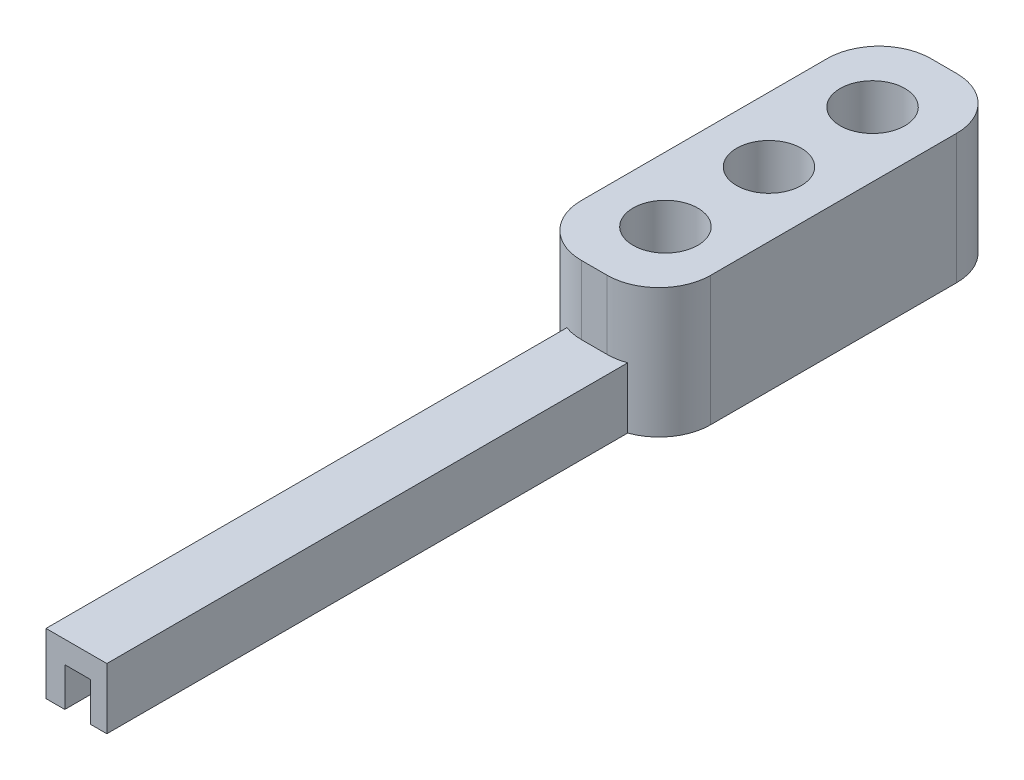
SolidWorks part; units mm, degrees
ref_plane "Front Plane" through (0, 0, 0) normal (0, 0, 1) x (1, 0, 0)
ref_plane "Top Plane" through (0, 0, 0) normal (0, 1, 0) x (1, 0, 0)
ref_plane "Right Plane" through (0, 0, 0) normal (1, 0, 0) x (0, 0, -1)
sketch "Sketch1" plane through (0, 0, 0) normal (0, 1, 0) x (1, 0, 0)
  line L1 (-4.8536, 23.9676) -> (5.1464, 23.9676)
  line L2 (-4.8536, 23.9676) -> (-4.8536, -3.0324)
  line L3 (-4.8536, -3.0324) -> (5.1464, -3.0324)
  line L4 (5.1464, 23.9676) -> (5.1464, -3.0324)
  dimension "D1" = 10
  dimension "D2" = 27
extrude "Boss-Extrude1" add sketch "Sketch1" along normal blind 10
sketch "Sketch2" plane through (0, 10, 0) normal (0, 1, 0) x (1, 0, 0)
  line L0 (5.1464, 23.9676) -> (-4.8536, 23.9676) construction
  line L1 (5.1464, -3.0324) -> (5.1464, 23.9676) construction
  circle A0 centre (0.1464, 18.4676) radius 2.5
  circle A1 centre (0.1464, 10.4676) radius 2.5
  circle A2 centre (0.1464, 2.4676) radius 2.5
  dimension "D1" = 5.5
  dimension "D2" = 5
  dimension "D3" = 5
  dimension "D4" = 3
extrude "Cut-Extrude1" cut sketch "Sketch2" against normal blind 10
sketch "Sketch3" plane through (0, 0, 3.0324) normal (0, 0, 1) x (1, 0, 0)
  line L0 (-4.8536, 0) -> (5.1464, 0) construction
  line L1 (-2.2036, 0) -> (2.4964, 0)
  line L2 (-2.2036, 0) -> (-2.2036, 4.7)
  line L3 (-2.2036, 4.7) -> (2.4964, 4.7)
  line L4 (2.4964, 0) -> (2.4964, 4.7)
  line L5 (5.1464, 10) -> (5.1464, 0) construction
  line L6 (-4.8536, 10) -> (-4.8536, 0) construction
  dimension "D1" = 2.65
  dimension "D2" = 2.65
  dimension "D3" = 4.7
extrude "Boss-Extrude2" add sketch "Sketch3" along normal blind 40
sketch "Sketch4" plane through (0, 0, 0) normal (0, -1, 0) x (-1, 0, 0)
  line L0 (2.2036, -43.0324) -> (-2.4964, -43.0324) construction
  line L1 (-1.2464, -43.0324) -> (0.7536, -43.0324)
  line L2 (-1.2464, -43.0324) -> (-1.2464, 18.9676)
  line L4 (0.7536, -43.0324) -> (0.7536, 18.9676)
  line L6 (-2.4964, -43.0324) -> (-2.4964, -3.0324) construction
  line L8 (-1.2464, 18.9676) -> (0.7536, 18.9676)
  line L9 (-5.1464, 23.9676) -> (4.8536, 23.9676) construction
  dimension "D1" = 1.25
  dimension "D2" = 2
  dimension "D3" = 5
extrude "Cut-Extrude3" cut sketch "Sketch4" against normal blind 3
fillet "Fillet1" radius 4 4 edges at (5.1464, 5, 3.0324) (-4.8536, 5, 3.0324) (-4.8536, 5, -23.9676) (5.1464, 5, -23.9676)
sketch "Sketch5" plane through (0, 0, 0) normal (0, -1, 0) x (-1, 0, 0)
  circle A0 centre (-0.1464, 18.4676) radius 3
  circle A1 centre (-0.1464, 10.4676) radius 3
  circle A2 centre (-0.1464, 2.4676) radius 3
  dimension "D1" = 6
  dimension "D2" = 3
extrude "Cut-Extrude4" cut sketch "Sketch5" against normal blind 3
sketch "Sketch6" plane through (0, 0, 0) normal (0, -1, 0) x (-1, 0, 0)
  line L2 (-0.1464, 18.4676) -> (-0.1464, 18.9676)
  line L3 (-0.1464, 18.9676) -> (4.8536, 18.9676)
  line L4 (4.8536, 18.4676) -> (4.8536, 18.9676)
  line L6 (-0.1464, 10.4676) -> (-0.1464, 10.9676)
  line L7 (-0.1464, 10.9676) -> (4.8536, 10.9676)
  line L8 (4.8536, 10.4676) -> (4.8536, 10.9676)
  line L10 (-0.1464, 2.4676) -> (-0.1464, 2.9676)
  line L11 (-0.1464, 2.9676) -> (4.8536, 2.9676)
  line L12 (4.8536, 2.4676) -> (4.8536, 2.9676)
  line L14 (-0.1464, 18.4676) -> (-0.1464, 17.9676)
  line L15 (-0.1464, 17.9676) -> (4.8536, 17.9676)
  line L16 (4.8536, 18.4676) -> (4.8536, 17.9676)
  line L18 (-0.1464, 10.4676) -> (-0.1464, 9.9676)
  line L19 (-0.1464, 9.9676) -> (4.8536, 9.9676)
  line L20 (4.8536, 10.4676) -> (4.8536, 9.9676)
  line L22 (-0.1464, 2.4676) -> (-0.1464, 1.9676)
  line L23 (-0.1464, 1.9676) -> (4.8536, 1.9676)
  line L24 (4.8536, 2.4676) -> (4.8536, 1.9676)
  dimension "D1" = 0.5
  dimension "D2" = 0.5
  dimension "D3" = 0.5
  dimension "D4" = 0.5
  dimension "D5" = 0.5
  dimension "D6" = 0.5
  dimension "D7" = 5
  dimension "D8" = 5
  dimension "D9" = 5
extrude "Cut-Extrude5" cut sketch "Sketch6" against normal blind 3
